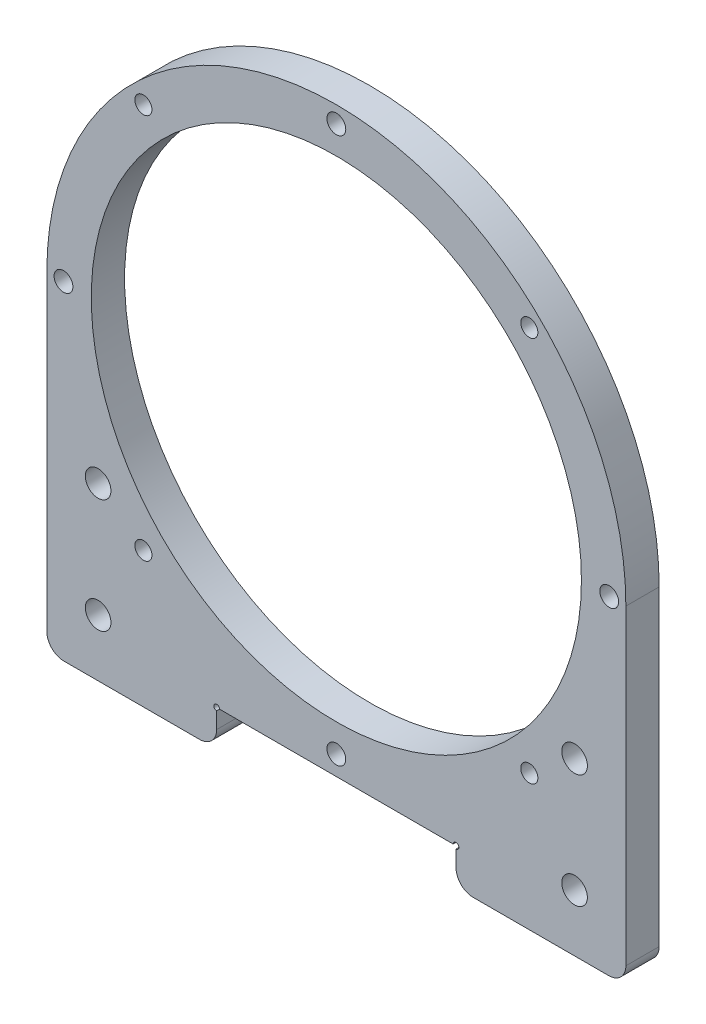
SolidWorks part; units mm, degrees
material "Acrylic (Medium-high impact)"
ref_plane "Front Plane" through (0, 0, 0) normal (0, 0, 1) x (1, 0, 0)
ref_plane "Top Plane" through (0, 0, 0) normal (0, 1, 0) x (1, 0, 0)
ref_plane "Right Plane" through (0, 0, 0) normal (1, 0, 0) x (0, 0, -1)
sketch "Sketch1" plane through (0, 0, 0) normal (0, 0, 1) x (1, 0, 0)
  line L0 (-50.8, 0) -> (-50.8, -57.658)
  line L1 (-50.8, 0) -> (-44.958, 0) construction
  line L2 (0, 0) -> (0, -57.658) construction
  line L4 (50.8, 0) -> (50.8, -57.658)
  line L5 (-33.8556, 33.8556) -> (0, 0) construction
  line L8 (0, 0) -> (0, 47.879) construction
  line L12 (-50.8, -57.658) -> (50.8, -57.658)
  line L16 (-41.8, -57.658) -> (-41.8, -47.658) construction
  line L17 (-41.8, -47.658) -> (-41.8, -27.658) construction
  circle A0 centre (41.8, -47.658) radius 2.25
  circle A1 centre (0, 0) radius 44.958
  arc A2 (-50.8, 0) -> (50.8, 0) centre (0, 0) cw
  circle A3 centre (-47.879, 0) radius 1.65
  circle A4 centre (0, 47.879) radius 1.65
  circle A5 centre (41.8, -27.658) radius 2.25
  circle A6 centre (47.879, 0) radius 1.65
  circle A7 centre (0, -47.879) radius 1.65
  circle A11 centre (-33.8556, 33.8556) radius 1.5
  circle A12 centre (33.8556, 33.8556) radius 1.5
  circle A13 centre (33.8556, -33.8556) radius 1.5
  circle A14 centre (-33.8556, -33.8556) radius 1.5
  circle A16 centre (-41.8, -27.658) radius 2.25
  circle A17 centre (-41.8, -47.658) radius 2.25
  point P29 (0, 0)
  point P46 (0, 0)
  dimension "D2" = 89.916
  dimension "D5" = 3.3
  dimension "D6" = 4
  dimension "D7" = 45
  dimension "D14" = 3
  dimension "D19" = 4.5
  dimension "D3" = 57.658
  dimension "D4" = 101.6
  dimension "D20" = 20
  dimension "D21" = 10
  dimension "D22" = 9
  dimension "D15" = 4
extrude "Boss-Extrude1" add sketch "Sketch1" along normal blind 5.842
sketch "Sketch2" plane through (0, 0, 5.842) normal (0, 0, 1) x (1, 0, 0)
  circle A0 centre (0, 0) radius 43
  circle A1 centre (0, 0) radius 44.958 construction
  circle A2 centre (0, 0) radius 44.958
  dimension "D1" = 86
extrude "Boss-Extrude2" add sketch "Sketch2" against normal through all
sketch "Sketch3" plane through (0, 0, 5.842) normal (0, 0, 1) x (1, 0, 0)
  line L0 (0, -57.658) -> (0, -51.308) construction
  line L1 (-50.8, -57.658) -> (50.8, -57.658) construction
  line L3 (-21, -57.658) -> (21, -57.658)
  line L4 (-21, -57.658) -> (-21, -51.308)
  line L5 (-21, -51.308) -> (21, -51.308)
  line L6 (21, -57.658) -> (21, -51.308)
  dimension "D1" = 6.35
  dimension "D2" = 42
extrude "Cut-Extrude1" cut sketch "Sketch3" against normal through all
sketch "Sketch4" plane through (0, 0, 5.842) normal (0, 0, 1) x (1, 0, 0)
  circle A0 centre (-21, -51.308) radius 0.5
  circle A1 centre (21, -51.308) radius 0.5
  dimension "D1" = 1
extrude "Cut-Extrude2" cut sketch "Sketch4" against normal through all
fillet "Fillet1" radius 3 4 edges at (50.8, -57.658, 2.921) (21, -57.658, 2.921) (-21, -57.658, 2.921) (-50.8, -57.658, 2.921)
